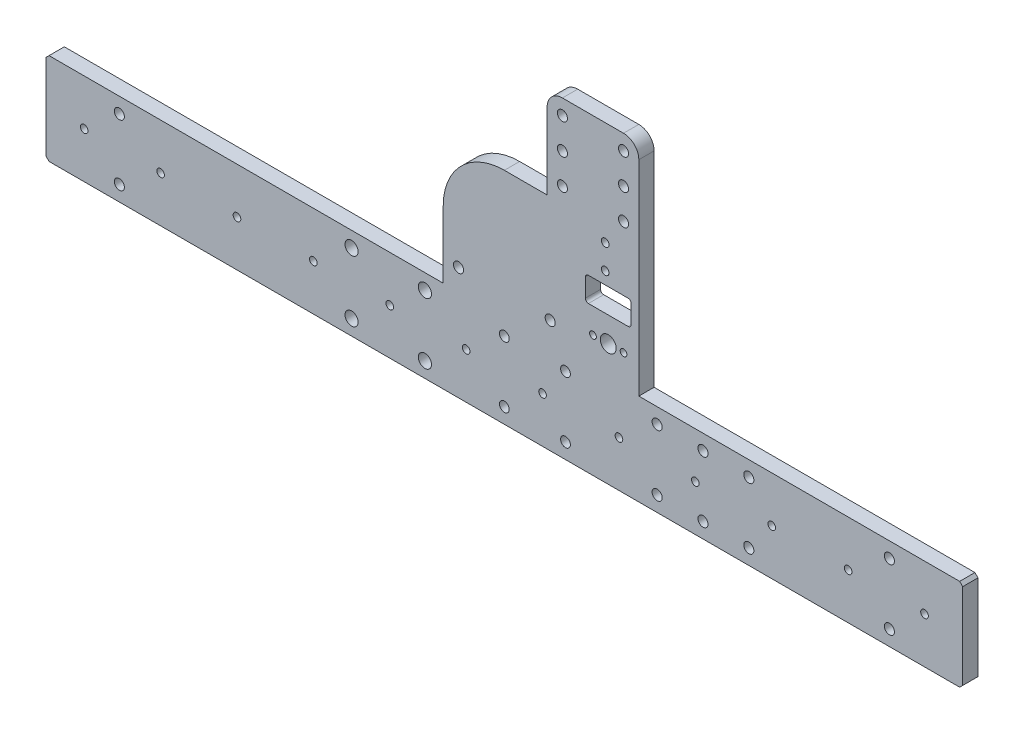
SolidWorks part; units mm, degrees
material "5052-O"
ref_plane "前基準面" through (0, 0, 0) normal (0, 0, 1) x (1, 0, 0)
ref_plane "上基準面" through (0, 0, 0) normal (0, 1, 0) x (1, 0, 0)
ref_plane "右基準面" through (0, 0, 0) normal (1, 0, 0) x (0, 0, -1)
sketch "草圖1" plane through (0, 0, 0) normal (0, 0, 1) x (1, 0, 0)
  line L1 (-150, -15) -> (150, -15)
  line L2 (-150, -15) -> (-150, 15)
  line L3 (-150, 15) -> (150, 15)
  line L4 (150, -15) -> (150, 15)
  line L5 (-150, -15) -> (150, 15) construction
  line L6 (-150, 15) -> (150, -15) construction
  point P0 (0, 0)
  dimension "D1" = 300
  dimension "D2" = 30
extrude "填料-伸長1" add sketch "草圖1" along normal blind 5
chamfer "導角1" distance 1 angle 45 4 edges at (150, -15, 2.5) (150, 15, 2.5) (-150, -15, 2.5) (-150, 15, 2.5)
hole_wizard "M3 餘隙孔1" positions "草圖7" profile "草圖8" hole size "M3" standard "Ansi Metric" end condition through all
sketch "草圖7" plane through (0, 0, 5) normal (0, 0, 1) x (1, 0, 0)
  line L0 (0, 0) -> (10, 0) construction
  line L4 (0, -10) -> (20, -10) construction
  line L5 (0, -10) -> (0, 10) construction
  line L6 (0, 10) -> (20, 10) construction
  line L7 (20, -10) -> (20, 10) construction
  line L8 (0, -10) -> (20, 10) construction
  line L9 (0, 10) -> (20, -10) construction
  point P9 (20, 10)
  point P60 (0, -10)
  point P61 (0, 10)
  point P62 (20, -10)
  dimension "D1" = 10
  dimension "D2" = 20
  dimension "D3" = 20
sketch "草圖8" plane through (20, -10, 5) normal (1, 0, 0) x (0, -1, 0)
  line L0 (0, 0) -> (0, 5)
  line L1 (0, 5) -> (1.6, 5)
  line L2 (1.6, 5) -> (1.6, 0)
  line L5 (1.6, 0) -> (0, 0)
  line L11 (0, -6.35) -> (0, 107.95) construction
  dimension "貫穿孔直徑" = 3.2
  dimension "貫穿孔深度" = 5
hole_wizard "M3x0.5 螺紋孔1" positions "草圖3" profile "草圖4" tap size "M3x0.5" standard "Ansi Metric" end condition through all
sketch "草圖3" plane through (0, 0, 5) normal (0, 0, 1) x (1, 0, 0)
  line L0 (-12.5, 0) -> (12.5, 0) construction
  point P0 (-12.5, 0)
  dimension "D1" = 25
sketch "草圖4" plane through (-12.5, 0, 5) normal (1, 0, 0) x (0, -1, 0)
  line L0 (0, 0) -> (0, 5)
  line L1 (0, 5) -> (1.25, 5)
  line L2 (1.25, 5) -> (1.25, 0)
  line L5 (1.25, 0) -> (0, 0)
  line L11 (0, -6.35) -> (0, 107.95) construction
  dimension "貫穿螺孔鑽直徑" = 2.5
  dimension "貫穿螺孔鑽深度" = 5
hole_wizard "M4x0.7 螺紋孔1" positions "草圖9" profile "草圖10" tap size "M4x0.7" standard "Ansi Metric" end condition through all
sketch "草圖9" plane through (0, 0, 5) normal (0, 0, 1) x (1, 0, 0)
  line L1 (50, -10) -> (80, -10) construction
  line L2 (50, -10) -> (50, 10) construction
  line L3 (50, 10) -> (80, 10) construction
  line L4 (80, -10) -> (80, 10) construction
  line L5 (50, -10) -> (80, 10) construction
  line L6 (50, 10) -> (80, -10) construction
  line L7 (0, 0) -> (65, 0) construction
  point P2 (80, 10)
  point P55 (50, -10)
  point P56 (50, 10)
  point P57 (80, -10)
  point P68 (65, 0)
  point P78 (65, 10)
  point P80 (65, -10)
  dimension "D1" = 30
  dimension "D2" = 20
  dimension "D3" = 65
sketch "草圖10" plane through (80, 10, 5) normal (1, 0, 0) x (0, -1, 0)
  line L0 (0, 0) -> (0, 5)
  line L1 (0, 5) -> (1.65, 5)
  line L2 (1.65, 5) -> (1.65, 0)
  line L5 (1.65, 0) -> (0, 0)
  line L11 (0, -6.35) -> (0, 107.95) construction
  dimension "砮 脸ふ苝 畖" = 3.3
  dimension "砮 脸ふ苝瞏 " = 5
hole_wizard "M4x0.7 螺紋孔2" positions "草圖11" profile "草圖12" tap size "M4x0.7" standard "Ansi Metric" end condition through all
sketch "草圖11" plane through (0, 0, 5) normal (0, 0, 1) x (1, 0, 0)
  line L0 (-150, 0) -> (-126, 0) construction
  line L1 (-150, 14) -> (-150, -14) construction
  line L4 (-126, -10) -> (-126, 10) construction
  point P9 (-126, -10)
  point P10 (-126, 10)
  dimension "D1" = 20
  dimension "D2" = 24
sketch "草圖12" plane through (-126, 10, 5) normal (1, 0, 0) x (0, -1, 0)
  line L0 (0, 0) -> (0, 5)
  line L1 (0, 5) -> (1.65, 5)
  line L2 (1.65, 5) -> (1.65, 0)
  line L5 (1.65, 0) -> (0, 0)
  line L11 (0, -6.35) -> (0, 107.95) construction
  dimension "貫穿螺孔鑽直徑" = 3.3
  dimension "貫穿螺孔鑽深度" = 5
pattern_linear "直線複製排列1" count 6 spacing 25 along (-1, 0, 0) count 7 spacing 25 along (1, 0, 0) of "M3x0.5 螺紋孔1"
mirror "鏡射1" about plane through (0, 0, 0) normal (1, 0, 0) of "M4x0.7 螺紋孔2"
sketch "草圖16" plane through (0, 0, 0) normal (0, 0, 1) x (1, 0, 0)
  line L0 (-20, 15) -> (44, 15)
  line L1 (149, 15) -> (-149, 15) construction
  line L4 (-20, 37) -> (-20, 15)
  line L5 (0, 0) -> (0, 57) construction
  line L9 (44, 15) -> (44, 57)
  line L10 (44, 57) -> (0, 57)
  arc A1 (-20, 37) -> (0, 57) centre (0, 37) cw
  dimension "D3" = 22
  dimension "D1" = 20
  dimension "D2" = 57
  dimension "D4" = 44
extrude "填料-伸長3" add sketch "草圖16" along normal through all
sketch "草圖13" plane through (0, 0, 0) normal (0, 0, 1) x (1, 0, 0)
  circle A1 centre (34, 24.8) radius 2.6
  dimension "D1" = 11.9701
  dimension "D2" = 5.2
  dimension "D3" = 24.8
  dimension "D4" = 34
  dimension "D5" = 34
extrude "除料-伸長2" cut sketch "草圖13" along normal through all
hole_wizard "M2 餘隙孔1" positions "草圖14" profile "草圖15" hole size "M2" standard "Ansi Metric" end condition through all
sketch "草圖14" plane through (0, 0, 5) normal (0, 0, 1) x (1, 0, 0)
  line L1 (29, 24.8) -> (39, 24.8) construction
  circle A2 centre (34, 24.8) radius 2.6 construction
  point P1 (29, 24.8)
  point P2 (39, 24.8)
  point P17 (34, 24.8)
  dimension "D1" = 10
sketch "草圖15" plane through (29, 24.8, 5) normal (1, 0, 0) x (0, -1, 0)
  line L0 (0, 0) -> (0, 5)
  line L1 (0, 5) -> (1.1, 5)
  line L2 (1.1, 5) -> (1.1, 0)
  line L5 (1.1, 0) -> (0, 0)
  line L11 (0, -6.35) -> (0, 107.95) construction
  dimension "貫穿孔直徑" = 2.2
  dimension "貫穿孔深度" = 5
hole_wizard "M4x0.7 螺紋孔3" positions "草圖19" profile "草圖20" tap size "M4x0.7" standard "Ansi Metric" end condition through all
sketch "草圖19" plane through (0, 0, 5) normal (0, 0, 1) x (1, 0, 0)
  line L0 (0, 57) -> (0, 22) construction
  line L4 (-15, 22) -> (15, 22) construction
  point P9 (-15, 22)
  point P10 (15, 22)
  dimension "D1" = 30
  dimension "D2" = 22
sketch "草圖20" plane through (15, 22, 5) normal (1, 0, 0) x (0, -1, 0)
  line L0 (0, 0) -> (0, 5)
  line L1 (0, 5) -> (1.65, 5)
  line L2 (1.65, 5) -> (1.65, 0)
  line L5 (1.65, 0) -> (0, 0)
  line L11 (0, -6.35) -> (0, 107.95) construction
  dimension "貫穿螺孔鑽直徑" = 3.3
  dimension "貫穿螺孔鑽深度" = 5
hole_wizard "M4 餘隙孔1" positions "草圖21" profile "草圖22" hole size "M4" standard "Ansi Metric" end condition through all
sketch "草圖21" plane through (0, 0, 5) normal (0, 0, 1) x (1, 0, 0)
  line L0 (0, 0) -> (-38, 0) construction
  line L4 (-50, -10) -> (-26, -10) construction
  line L5 (-50, -10) -> (-50, 10) construction
  line L6 (-50, 10) -> (-26, 10) construction
  line L7 (-26, -10) -> (-26, 10) construction
  line L8 (-50, -10) -> (-26, 10) construction
  line L9 (-50, 10) -> (-26, -10) construction
  point P11 (-26, 10)
  point P60 (-50, -10)
  point P61 (-50, 10)
  point P62 (-26, -10)
  dimension "D1" = 38
  dimension "D2" = 24
  dimension "D3" = 20
sketch "草圖22" plane through (-26, -10, 5) normal (1, 0, 0) x (0, -1, 0)
  line L0 (0, 0) -> (0, 5)
  line L1 (0, 5) -> (2.15, 5)
  line L2 (2.15, 5) -> (2.15, 0)
  line L5 (2.15, 0) -> (0, 0)
  line L11 (0, -6.35) -> (0, 107.95) construction
  dimension "貫穿孔直徑" = 4.3
  dimension "貫穿孔深度" = 5
hole_wizard "M3x0.5 螺紋孔2" positions "草圖23" profile "草圖24" tap size "M3x0.5" standard "Ansi Metric" end condition through all
sketch "草圖23" plane through (0, 0, 5) normal (0, 0, 1) x (1, 0, 0)
  line L0 (33, 53) -> (33, 45) construction
  line L3 (44, 15) -> (44, 57) construction
  line L4 (44, 57) -> (0, 57) construction
  point P0 (33, 53)
  point P1 (33, 45)
  dimension "D1" = 11
  dimension "D2" = 8
  dimension "D3" = 4
sketch "草圖24" plane through (33, 53, 5) normal (1, 0, 0) x (0, -1, 0)
  line L0 (0, 0) -> (0, 5)
  line L1 (0, 5) -> (1.25, 5)
  line L2 (1.25, 5) -> (1.25, 0)
  line L5 (1.25, 0) -> (0, 0)
  line L11 (0, -6.35) -> (0, 107.95) construction
  dimension "貫穿螺孔鑽直徑" = 2.5
  dimension "貫穿螺孔鑽深度" = 5
sketch "草圖25" plane through (0, 0, 5) normal (0, 0, 1) x (1, 0, 0)
  line L0 (44, 15) -> (44, 57) construction
  line L1 (41.5, 41) -> (26.5, 41)
  line L2 (41.5, 41) -> (41.5, 33)
  line L3 (41.5, 33) -> (26.5, 33)
  line L4 (26.5, 41) -> (26.5, 33)
  line L5 (44, 57) -> (0, 57) construction
  dimension "D1" = 15
  dimension "D2" = 8
  dimension "D3" = 2.5
  dimension "D4" = 16
extrude "除料-伸長3" cut sketch "草圖25" against normal through all and the other way through all
fillet "圓角1" radius 1 4 edges at (41.5, 33, 2.5) (41.5, 41, 2.5) (26.5, 41, 2.5) (26.5, 33, 2.5)
sketch "草圖26" plane through (0, 57, 0) normal (0, 1, 0) x (1, 0, 0)
  line L0 (44, -5) -> (0, -5) construction
  line L1 (44, 0) -> (14, 0)
  line L2 (44, 0) -> (44, -5)
  line L3 (44, -5) -> (14, -5)
  line L4 (14, 0) -> (14, -5)
  dimension "D1" = 30
extrude "填料-伸長4" add sketch "草圖26" along normal blind 30
sketch "草圖27" plane through (0, 0, 5) normal (0, 0, 1) x (1, 0, 0)
  line L0 (14, 87) -> (44, 87) construction
  line L1 (14, 87) -> (14, 57) construction
  circle A0 centre (19, 82) radius 1.65
  dimension "D1" = 3.3
  dimension "D2" = 5
  dimension "D3" = 5
extrude "除料-伸長4" cut sketch "草圖27" against normal through all
pattern_linear "直線複製排列2" count 2 spacing 20 along (1, 0, 0) count 3 spacing 10 along (0, -1, 0) of "除料-伸長4"
fillet "圓角2" radius 5 2 edges at (44, 87, 2.5) (14, 87, 2.5)
